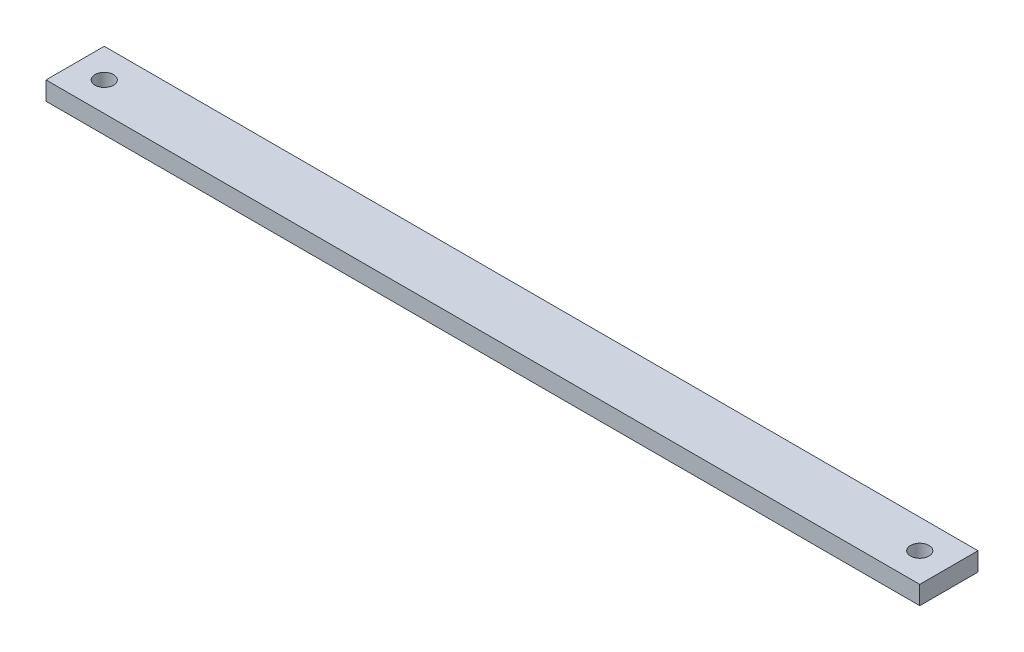
SolidWorks part; units mm, degrees
material "ABS"
ref_plane "Front Plane" through (0, 0, 0) normal (0, 0, 1) x (1, 0, 0)
ref_plane "Top Plane" through (0, 0, 0) normal (0, 1, 0) x (1, 0, 0)
ref_plane "Right Plane" through (0, 0, 0) normal (1, 0, 0) x (0, 0, -1)
sketch "Sketch1" plane through (0, 0, 0) normal (0, 1, 0) x (1, 0, 0)
  line L1 (-150, 10) -> (150, 10)
  line L2 (-150, 10) -> (-150, -10)
  line L3 (-150, -10) -> (150, -10)
  line L4 (150, 10) -> (150, -10)
  point P4 (0, -10)
  point P5 (0, 10)
  point P9 (150, 0)
  dimension "D1" = 300
  dimension "D2" = 20
extrude "Boss-Extrude1" add sketch "Sketch1" along normal blind 6.35
sketch "Sketch2" plane through (0, 0, 0) normal (0, -1, 0) x (-1, 0, 0)
  line L0 (-55, 0) -> (55, 0) construction
  line L1 (150, 10) -> (150, -10) construction
  circle A0 centre (140, 0) radius 3.175
  dimension "D1" = 6.35
  dimension "D2" = 10
extrude "Cut-Extrude1" cut sketch "Sketch2" against normal up to surface (6.35 mm away) up to face at (0, 6.35, 0)
mirror "Mirror1" about plane through (0, 0, 0) normal (1, 0, 0) of "Cut-Extrude1"
